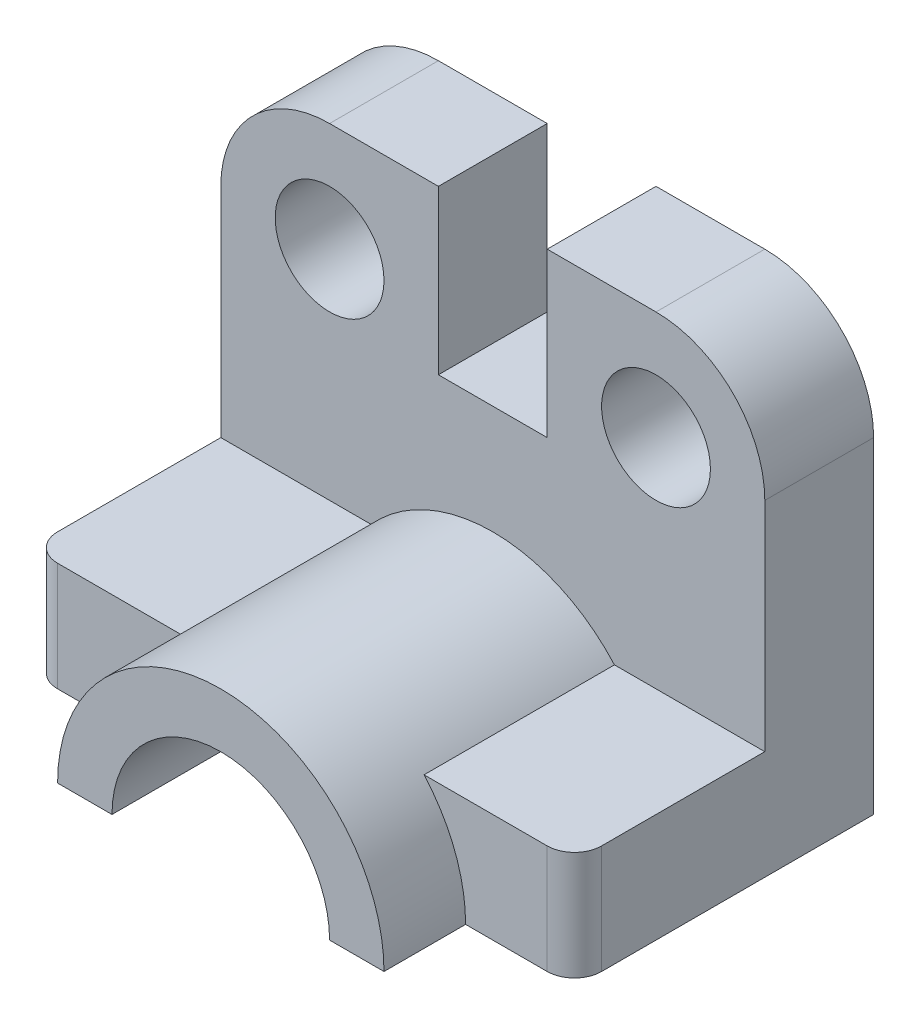
SolidWorks part; units mm, degrees
ref_plane "前基準面" through (0, 0, 0) normal (0, 0, 1) x (1, 0, 0)
ref_plane "上基準面" through (0, 0, 0) normal (0, 1, 0) x (1, 0, 0)
ref_plane "右基準面" through (0, 0, 0) normal (1, 0, 0) x (0, 0, -1)
sketch "草圖1" plane through (0, 0, 0) normal (0, 0, 1) x (1, 0, 0)
  line L0 (0, 37.5374) -> (0, -23.6878) construction
  line L1 (-50, 80) -> (-10, 80)
  line L2 (-50, 80) -> (-50, 0)
  line L3 (-50, 0) -> (50, 0)
  line L4 (50, 80) -> (50, 0)
  line L5 (10, 80) -> (50, 80)
  line L7 (-10, 80) -> (-10, 50)
  line L8 (-10, 50) -> (10, 50)
  line L9 (10, 80) -> (10, 50)
  circle A0 centre (-30, 60) radius 10
  circle A1 centre (30, 60) radius 10
  point P11 (0, 0)
  dimension "D3" = 20
  dimension "D4" = 20
  dimension "D1" = 100
  dimension "D2" = 80
  dimension "D5" = 60
  dimension "D6" = 60
  dimension "D7" = 20
  dimension "D8" = 30
extrude "填料-伸長1" add sketch "草圖1" along normal blind 20
fillet "圓角1" radius 20 2 edges at (-50, 80, 10) (50, 80, 10)
sketch "草圖2" plane through (0, 0, 20) normal (0, 0, 1) x (1, 0, 0)
  line L0 (-50, 0) -> (50, 0) construction
  line L1 (-30, 0) -> (30, 0)
  circle A0 centre (0, 0) radius 20
  circle A1 centre (0, 0) radius 30
  line M5 (-50, 0) -> (50, 0)
  dimension "D1" = 40
  dimension "D2" = 60
extrude "填料-伸長2" add sketch "草圖2" along normal blind 50 contours A1 A0 M5
sketch "草圖3" plane through (0, 0, 20) normal (0, 0, 1) x (1, 0, 0)
  line L0 (-50, 60) -> (-50, 0) construction
  line L1 (-50, 20) -> (50, 20)
  line L2 (-50, 20) -> (-50, 0)
  line L3 (-50, 0) -> (50, 0)
  line L4 (50, 20) -> (50, 0)
  dimension "D1" = 20
extrude "填料-伸長3" add sketch "草圖3" along normal blind 35
fillet "圓角2" radius 5 2 edges at (50, 10, 55) (-50, 10, 55)
sketch "草圖4" plane through (0, 0, 70) normal (0, 0, 1) x (1, 0, 0)
  line L0 (-20, 0) -> (20, 0)
  line L2 (20, 0) -> (30, 0)
  line L3 (-30, 0) -> (-20, 0)
  line L4 (20, 0) -> (30, 0)
  line L5 (-30, 0) -> (-20, 0)
  arc A2 (30, 0) -> (-30, 0) centre (0, 0) ccw
  arc A3 (20, 0) -> (-20, 0) centre (0, 0) ccw
  arc A4 (30, 0) -> (-30, 0) centre (0, 0) ccw
  arc A5 (20, 0) -> (-20, 0) centre (0, 0) ccw
  arc M8 (-20, 0) -> (20, 0) centre (0, 0) cw
  dimension "D1" = 0
extrude "除料-伸長1" cut sketch "草圖4" against normal up to surface (50 mm away) contours L0 M8 up to face at (-20, 60, 20)
